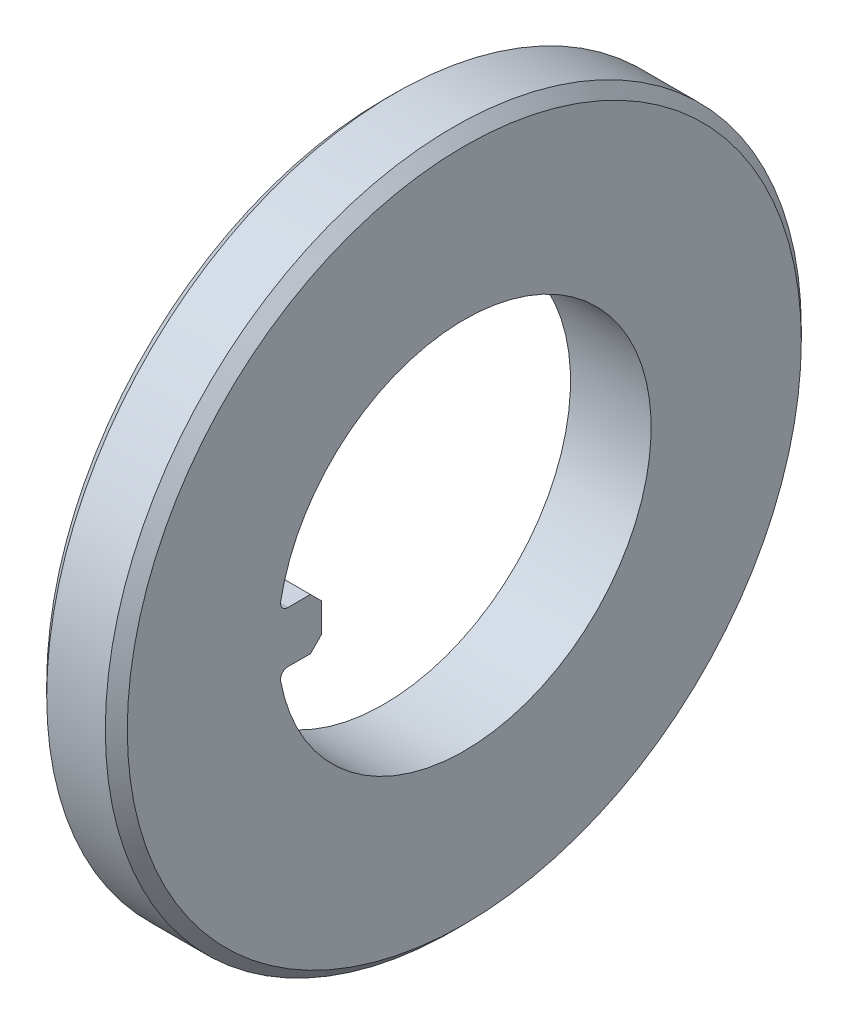
SolidWorks part; units mm, degrees
ref_plane "Alzado" through (0, 0, 0) normal (1, 0, 0) x (0, 1, 0)
ref_plane "Planta" through (0, 0, 0) normal (0, 0, 1) x (0, 1, 0)
ref_plane "Vista lateral" through (0, 0, 0) normal (0, 1, 0) x (-1, 0, 0)
sketch "Croquis1" plane through (0, 0, 0) normal (1, 0, 0) x (0, 1, 0)
  line L0 (0, 0) -> (0, 24.6476) construction
  line L1 (1.4, 10.1035) -> (1.4, 7.8)
  line L2 (1.4, 7.8) -> (-1.4, 7.8)
  line L3 (-1.4, 10.1035) -> (-1.4, 7.8)
  circle A0 centre (0, 0) radius 19
  arc A1 (-1.4, 10.1035) -> (1.4, 10.1035) centre (0, 0) ccw
  point P10 (0, 7.8)
  dimension "D1" = 38
  dimension "D2" = 20.4
  dimension "D3" = 7.8
  dimension "D4" = 1.4
extrude "Saliente-Extruir1" add sketch "Croquis1" along normal blind 4.4
chamfer "Chaflán1" distance 0.6 angle 45 2 edges at (0, 0, -19) (4.4, 0, -19)
chamfer "Chaflán2" distance 0.6 angle 45 2 edges at (2.2, 1.4, 7.8) (2.2, -1.4, 7.8)
fillet "Redondeo1" radius 0.4 2 edges at (2.2, -1.4, 10.1035) (2.2, 1.4, 10.1035)
